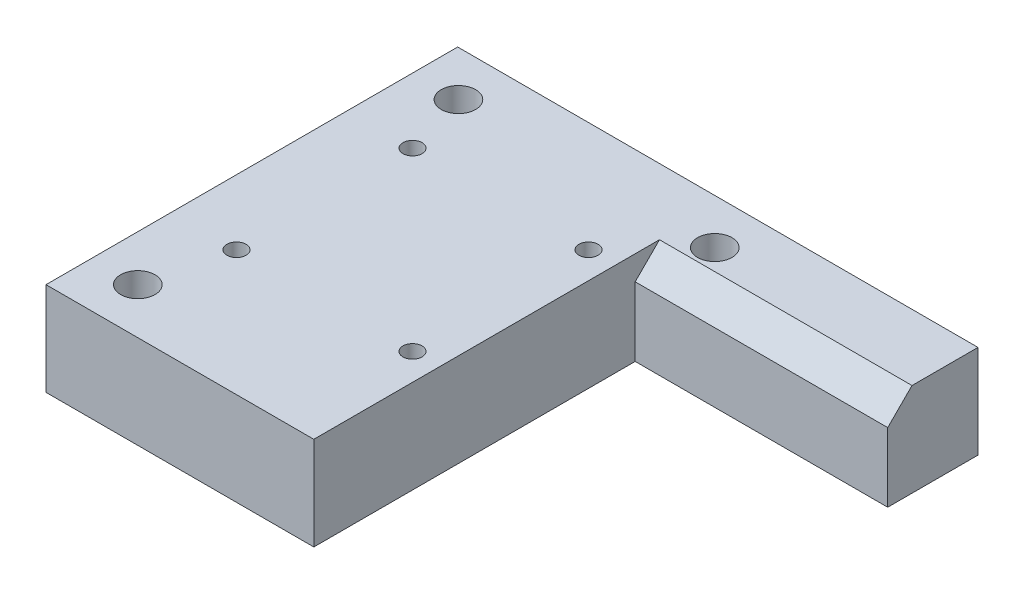
SolidWorks part; units mm, degrees
ref_plane "Front Plane" through (0, 0, 0) normal (0, 0, 1) x (1, 0, 0)
ref_plane "Top Plane" through (0, 0, 0) normal (0, 1, 0) x (1, 0, 0)
ref_plane "Right Plane" through (0, 0, 0) normal (1, 0, 0) x (0, 0, -1)
sketch "Sketch1" plane through (0, 0, 0) normal (0, 0, 1) x (1, 0, 0)
  line L1 (0, 0) -> (68, 0)
  line L2 (0, 0) -> (0, -12.192)
  line L3 (0, -12.192) -> (68, -12.192)
  line L4 (68, 0) -> (68, -12.192)
  dimension "D1" = 68
  dimension "D2" = 12.192
extrude "Boss-Extrude1" add sketch "Sketch1" along normal blind 11.8
sketch "Sketch2" plane through (0, 0, 0) normal (0, 1, 0) x (1, 0, 0)
  line L0 (68, -5.9) -> (0, -5.9) construction
  line L1 (68, -11.8) -> (68, 0) construction
  line L2 (45.5, 0) -> (45.5, -11.8) construction
  line L3 (68, 0) -> (0, 0) construction
  line L4 (68, -11.8) -> (0, -11.8) construction
  line L5 (0, -11.8) -> (0, 0) construction
  circle A0 centre (39.5, -5.9) radius 2.25
  circle A1 centre (6, -5.9) radius 2.25
  dimension "D2" = 4.5
  dimension "D3" = 4.5
  dimension "D4" = 6
  dimension "D5" = 6
  dimension "D1" = 45.5
extrude "Cut-Extrude1" cut sketch "Sketch2" against normal through all
sketch "Sketch3" plane through (0, 0, 0) normal (0, 1, 0) x (1, 0, 0)
  circle A0 centre (39.5, -5.9) radius 4.125
  circle A1 centre (6, -5.9) radius 4.125
  dimension "D1" = 8.25
  dimension "D2" = 8.25
extrude "Cut-Extrude2" cut sketch "Sketch3" against normal blind 7
sketch "Sketch4" plane through (0, 0, 11.8) normal (0, 0, 1) x (1, 0, 0)
  line L0 (0, -12.192) -> (68, -12.192) construction
  line L1 (0, 0) -> (35, 0)
  line L2 (0, 0) -> (0, -12.192)
  line L3 (0, -12.192) -> (35, -12.192)
  line L4 (35, 0) -> (35, -12.192)
  dimension "D1" = 35
extrude "Boss-Extrude2" add sketch "Sketch4" along normal blind 42
sketch "Sketch5" plane through (0, 0, 0) normal (0, 1, 0) x (1, 0, 0)
  line L0 (35, -53.8) -> (0, -53.8) construction
  line L1 (0, -53.8) -> (0, 0) construction
  circle A0 centre (6, -47.8) radius 2.25
  dimension "D1" = 4.5
  dimension "D2" = 6
  dimension "D3" = 6
extrude "Cut-Extrude3" cut sketch "Sketch5" against normal through all
sketch "Sketch6" plane through (0, 0, 0) normal (0, 1, 0) x (1, 0, 0)
  line L0 (35, -53.8) -> (0, -53.8) construction
  circle A0 centre (6, -47.8) radius 4.125
  dimension "D1" = 8.25
  dimension "D2" = 6
extrude "Cut-Extrude4" cut sketch "Sketch6" against normal blind 7
sketch "Sketch7" plane through (0, 0, 0) normal (0, 1, 0) x (1, 0, 0)
  circle A0 centre (8.5, -14.4002) radius 1.25
  circle A1 centre (8.4978, -37.4024) radius 1.25
  circle A2 centre (31.5, -37.4046) radius 1.25
  circle A3 centre (31.5022, -14.4024) radius 1.25
  dimension "D1" = 2.5
  dimension "D2" = 2.5
  dimension "D3" = 2.5
  dimension "D4" = 2.5
extrude "Cut-Extrude5" cut sketch "Sketch7" against normal up to next
chamfer "Chamfer1" distance 3.175 angle 45 1 edges
mirror "镜向1" about plane through (0, 0, 0) normal (0, 1, 0) of bodies 108
sketch "草图1" plane through (0, 0, 53.8) normal (0, 0, 1) x (1, 0, 0)
  line L1 (0, 0) -> (81.9559, 0)
  line L2 (0, 0) -> (0, -24.4116)
  line L3 (0, -24.4116) -> (81.9559, -24.4116)
  line L4 (81.9559, 0) -> (81.9559, -24.4116)
extrude "切除-拉伸1" cut sketch "草图1" against normal through all
